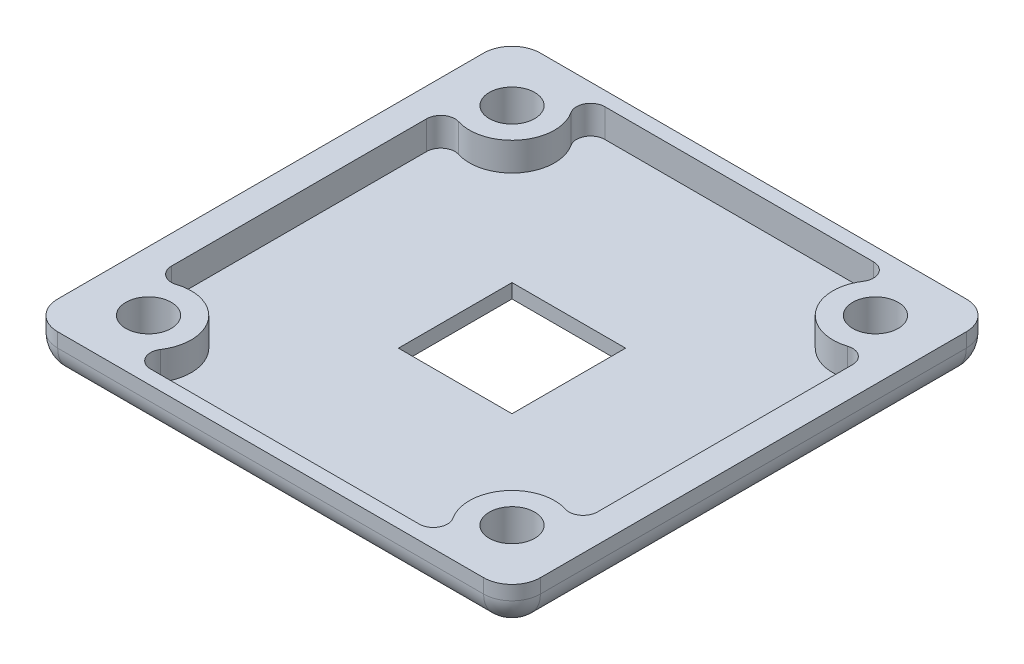
SolidWorks part; units mm, degrees
ref_plane "Front Plane" through (0, 0, 0) normal (0, 0, 1) x (1, 0, 0)
ref_plane "Top Plane" through (0, 0, 0) normal (0, 1, 0) x (1, 0, 0)
ref_plane "Right Plane" through (0, 0, 0) normal (1, 0, 0) x (0, 0, -1)
sketch "Sketch1" plane through (0, 0, 0) normal (0, 1, 0) x (1, 0, 0)
  line L1 (-13.4937, -13.4937) -> (13.4938, -13.4937)
  line L2 (-13.4937, -13.4937) -> (-13.4937, 13.4938)
  line L3 (-13.4937, 13.4938) -> (13.4938, 13.4938)
  line L4 (13.4938, -13.4937) -> (13.4938, 13.4938)
  line L5 (-13.4937, -13.4937) -> (13.4938, 13.4938) construction
  line L6 (-13.4937, 13.4938) -> (13.4938, -13.4937) construction
  point P0 (0, 0)
  dimension "D1" = 26.9875
extrude "Boss-Extrude1" add sketch "Sketch1" along normal blind 2.3813
sketch "Sketch2" plane through (0, 2.3813, 0) normal (0, 1, 0) x (1, 0, 0)
  line L1 (-3.175, -3.175) -> (3.175, -3.175)
  line L2 (-3.175, -3.175) -> (-3.175, 3.175)
  line L3 (-3.175, 3.175) -> (3.175, 3.175)
  line L4 (3.175, -3.175) -> (3.175, 3.175)
  line L5 (-3.175, -3.175) -> (3.175, 3.175) construction
  line L6 (-3.175, 3.175) -> (3.175, -3.175) construction
  point P0 (0, 0)
  dimension "D1" = 6.35
extrude "Cut-Extrude1" cut sketch "Sketch2" against normal through all
sketch "Sketch3" plane through (0, 2.3813, 0) normal (0, 1, 0) x (1, 0, 0)
  circle A0 centre (-10.16, 10.16) radius 1.27
  circle A1 centre (10.16, 10.16) radius 1.27
  circle A2 centre (10.16, -10.16) radius 1.27
  circle A3 centre (-10.16, -10.16) radius 1.27
  circle A4 centre (-10.16, 10.16) radius 1.905 construction
  circle A5 centre (-10.16, -10.16) radius 1.905 construction
  circle A6 centre (10.16, -10.16) radius 1.905 construction
  circle A7 centre (10.16, 10.16) radius 1.905 construction
  dimension "D1" = 2.54
extrude "Cut-Extrude2" cut sketch "Sketch3" against normal through all
sketch "Sketch4" plane through (0, 2.3813, 0) normal (0, 1, 0) x (1, 0, 0)
  line L0 (0, 0) -> (0, 4.4454) construction
  line L1 (0, 0) -> (-5.6884, 0) construction
  line L8 (-11.9062, -7.1312) -> (-11.9062, 7.1312)
  line L9 (-7.5084, 12.7) -> (7.5084, 12.7)
  line L10 (13.4938, 13.4938) -> (-13.4937, 13.4938) construction
  line L11 (-13.4937, 13.4938) -> (-13.4937, -13.4937) construction
  line L12 (11.9062, -7.1312) -> (11.9062, 7.1312)
  line L13 (-7.5084, -12.7) -> (7.5084, -12.7)
  arc A0 (-10.8744, 7.8884) -> (-8.1713, 11.4697) centre (-10.16, 10.16) ccw
  arc A4 (-8.1713, 11.4697) -> (-7.5084, 12.7) centre (-7.5084, 11.9063) cw
  arc A5 (-10.8744, 7.8884) -> (-11.9062, 7.1312) centre (-11.1125, 7.1312) ccw
  arc A6 (10.8744, 7.8884) -> (11.9062, 7.1312) centre (11.1125, 7.1312) cw
  arc A7 (10.8744, 7.8884) -> (8.1713, 11.4697) centre (10.16, 10.16) cw
  arc A8 (8.1713, 11.4697) -> (7.5084, 12.7) centre (7.5084, 11.9063) ccw
  arc A9 (8.1713, -11.4697) -> (7.5084, -12.7) centre (7.5084, -11.9063) cw
  arc A10 (10.8744, -7.8884) -> (8.1713, -11.4697) centre (10.16, -10.16) ccw
  arc A11 (10.8744, -7.8884) -> (11.9062, -7.1312) centre (11.1125, -7.1312) ccw
  arc A12 (-10.8744, -7.8884) -> (-11.9062, -7.1312) centre (-11.1125, -7.1312) cw
  arc A13 (-8.1713, -11.4697) -> (-7.5084, -12.7) centre (-7.5084, -11.9063) ccw
  arc A14 (-10.8744, -7.8884) -> (-8.1713, -11.4697) centre (-10.16, -10.16) cw
  point P8 (0, -12.7)
  point P9 (-12.537, 0)
  point P10 (0, 4.4454)
  point P17 (0, 12.7)
  point P20 (-11.9062, 0)
  point P26 (-11.9062, 0)
  point P29 (0, 12.7)
  point P44 (11.9062, 0)
  dimension "D1" = 0.7937
  dimension "D2" = 2.3813
  dimension "D3" = 0.7937
  dimension "D4" = 1.5875
extrude "Cut-Extrude3" cut sketch "Sketch4" against normal offset from surface (1.5875 mm away) 0.7937 up to face at (-10.16, 0, 11.43)
fillet "Fillet1" radius 1.5875 4 edges at (13.4938, 1.1906, 13.4937) (13.4938, 1.1906, -13.4938) (-13.4937, 1.1906, -13.4938) (-13.4937, 1.1906, 13.4937)
fillet "Fillet2" radius 1.5875 8 edges at (-13.0288, 0, 13.0288) (-13.4937, 0, 0) (-13.0288, 0, -13.0288) (0, 0, -13.4938) (13.0288, 0, -13.0288) (13.4938, 0, 0) (13.0288, 0, 13.0288) (0, 0, 13.4937)
